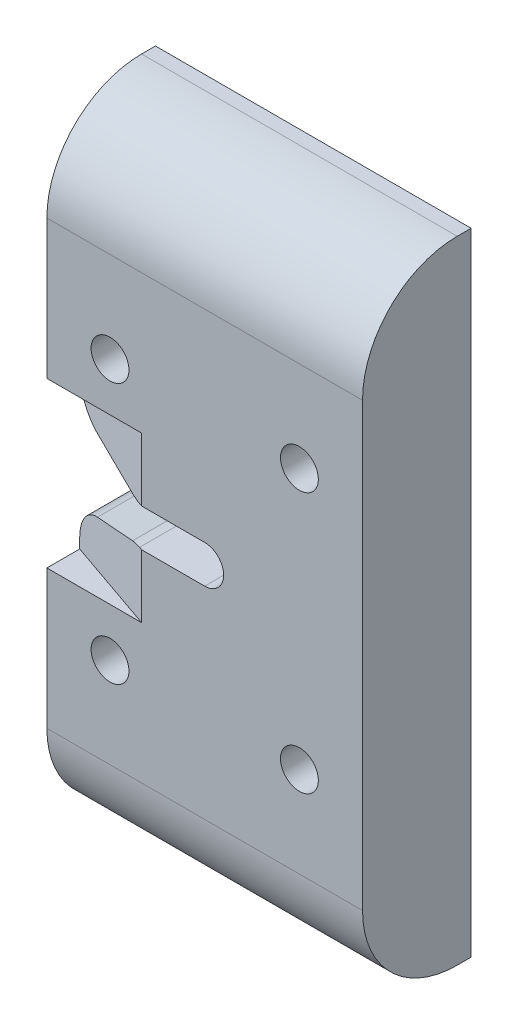
SolidWorks part; units mm, degrees
ref_plane "Спереди" through (0, 0, 0) normal (0, 0, 1) x (1, 0, 0)
ref_plane "Сверху" through (0, 0, 0) normal (0, 1, 0) x (1, 0, 0)
ref_plane "Справа" through (0, 0, 0) normal (1, 0, 0) x (0, 0, -1)
sketch "Эскиз1" plane through (0, 0, 0) normal (0, 0, 1) x (1, 0, 0)
  line L1 (0, 0) -> (50, 0)
  line L2 (0, 0) -> (0, 100)
  line L3 (0, 100) -> (50, 100)
  line L4 (50, 0) -> (50, 100)
  dimension "D1" = 100
  dimension "D2" = 50
extrude "Бобышка-Вытянуть1" add sketch "Эскиз1" along normal blind 17.2
fillet "Скругление1" radius 15 2 edges at (25, 0, 17.2) (25, 100, 17.2)
ref_plane "Плоскость1" through (0, 37, 0) normal (0, 1, 0) x (1, 0, 0)
sketch "Эскиз5" plane through (0, 37, 0) normal (0, 1, 0) x (1, 0, 0)
  line L0 (0, -17.2) -> (0, -12)
  line L1 (0, -2.2) -> (0, -17.2) construction
  line L2 (0, -12) -> (15, -17.2)
  line L3 (50, -17.2) -> (0, -17.2) construction
  line L4 (15, -17.2) -> (0, -17.2)
  dimension "D1" = 12
  dimension "D2" = 15
extrude "Вырез-Вытянуть3" cut sketch "Эскиз5" along normal blind 26
sketch "Эскиз6" plane through (0, 0, 17.2) normal (0, 0, 1) x (1, 0, 0)
  circle A0 centre (25, 50) radius 3
  dimension "D1" = 6
  dimension "D2" = 50
  dimension "D3" = 25
extrude "Вырез-Вытянуть4" cut sketch "Эскиз6" against normal through all
sketch "Эскиз7" plane through (0, 0, 0) normal (0, 0, -1) x (-1, 0, 0)
  line L1 (0, 100) -> (0, 0) construction
  line L2 (0, 57) -> (0, 43)
  line L4 (-25, 47) -> (-25, 53)
  line L5 (-25, 47) -> (-13.6464, 47)
  line L6 (-13.6464, 47) -> (0, 43)
  line L7 (-25, 53) -> (-13.6464, 53)
  line L8 (-13.6464, 53) -> (0, 57)
  circle A0 centre (-25, 50) radius 3 construction
  point P8 (0, 50)
  dimension "D1" = 14
  dimension "D2" = 0
extrude "Вырез-Вытянуть5" cut sketch "Эскиз7" against normal through all
fillet "Скругление2" radius 6 2 edges at (0, 43, 6) (0, 57, 6)
fillet "Скругление3" radius 6 2 edges at (13.6464, 47, 8.3654) (13.6464, 53, 8.3654)
sketch "Эскиз9" plane through (0, 0, 0) normal (0, 0, -1) x (-1, 0, 0)
  line L0 (-50, 0) -> (-50, 100) construction
  circle A0 centre (-40, 29.35) radius 3
  circle A1 centre (-10, 29.35) radius 3
  circle A2 centre (-10, 70.65) radius 3
  circle A3 centre (-40, 70.65) radius 3
  point P4 (-50, 50)
  dimension "D1" = 6
  dimension "D2" = 10
  dimension "D3" = 20.65
  dimension "D4" = 2
  dimension "D5" = 2
extrude "Вырез-Вытянуть6" cut sketch "Эскиз9" against normal through all
sketch "Эскиз10" plane through (0, 0, 0) normal (0, 0, -1) x (-1, 0, 0)
  circle A0 centre (-40, 29.35) radius 6
  circle A1 centre (-10, 29.35) radius 6
  circle A2 centre (-10, 70.65) radius 6
  circle A3 centre (-40, 70.65) radius 6
  dimension "D1" = 12
  dimension "D2" = 2
  dimension "D3" = 2
extrude "Вырез-Вытянуть7" cut sketch "Эскиз10" against normal blind 9
